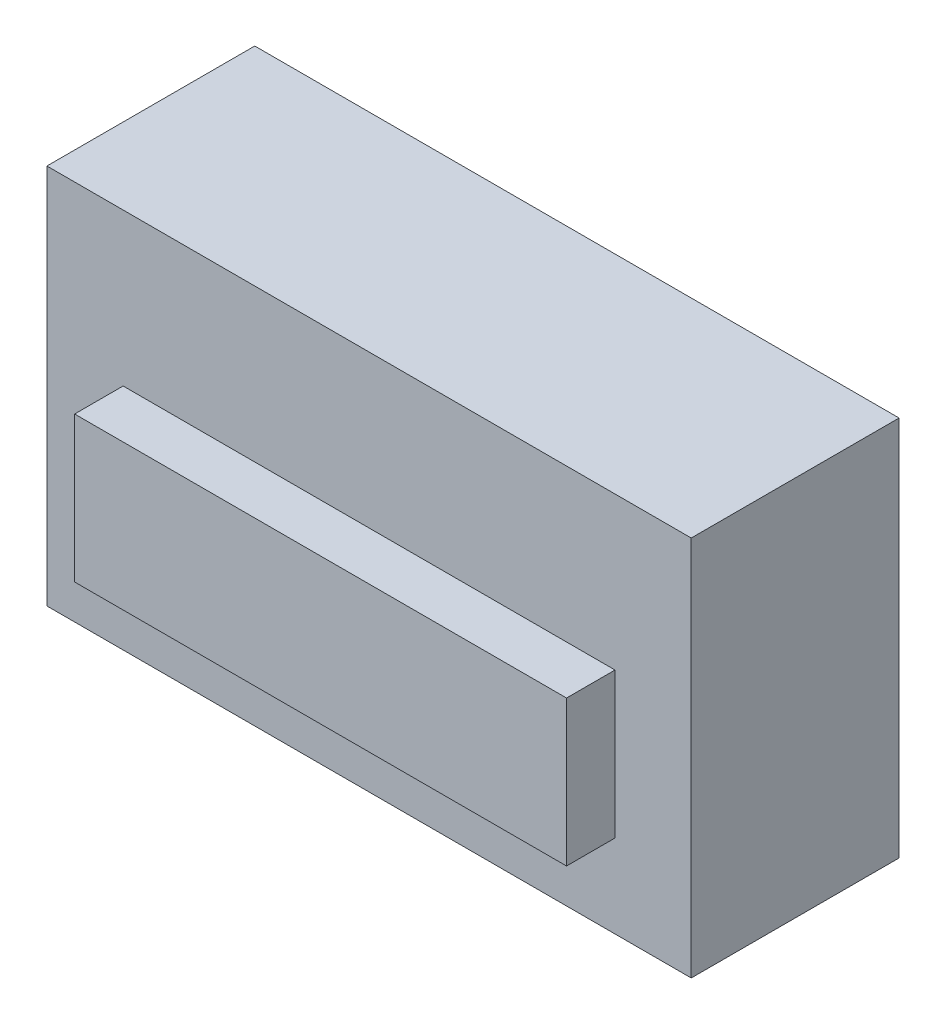
SolidWorks part; units mm, degrees
ref_plane "Front Plane" through (0, 0, 0) normal (0, 0, 1) x (1, 0, 0)
ref_plane "Top Plane" through (0, 0, 0) normal (0, 1, 0) x (1, 0, 0)
ref_plane "Right Plane" through (0, 0, 0) normal (1, 0, 0) x (0, 0, -1)
sketch "Sketch1" plane through (0, 0, 0) normal (0, 0, 1) x (1, 0, 0)
  line L1 (-46.5, 27.5) -> (46.5, 27.5)
  line L2 (-46.5, 27.5) -> (-46.5, -27.5)
  line L3 (-46.5, -27.5) -> (46.5, -27.5)
  line L4 (46.5, 27.5) -> (46.5, -27.5)
  line L5 (-46.5, 27.5) -> (46.5, -27.5) construction
  line L6 (-46.5, -27.5) -> (46.5, 27.5) construction
  point P0 (0, 0)
  dimension "D1" = 93
  dimension "D2" = 55
extrude "Boss-Extrude1" add sketch "Sketch1" along normal blind 30
sketch "Sketch2" plane through (0, 0, 30) normal (0, 0, 1) x (1, 0, 0)
  line L0 (-46.5, -27.5) -> (46.5, -27.5) construction
  line L1 (-35.5, 5.5) -> (35.5, 5.5)
  line L2 (-35.5, 5.5) -> (-35.5, -15.5)
  line L3 (-35.5, -15.5) -> (35.5, -15.5)
  line L4 (35.5, 5.5) -> (35.5, -15.5)
  point P0 (0, 0)
  dimension "D1" = 71
  dimension "D2" = 21
  dimension "D3" = 12
extrude "Boss-Extrude2" add sketch "Sketch2" along normal blind 7
